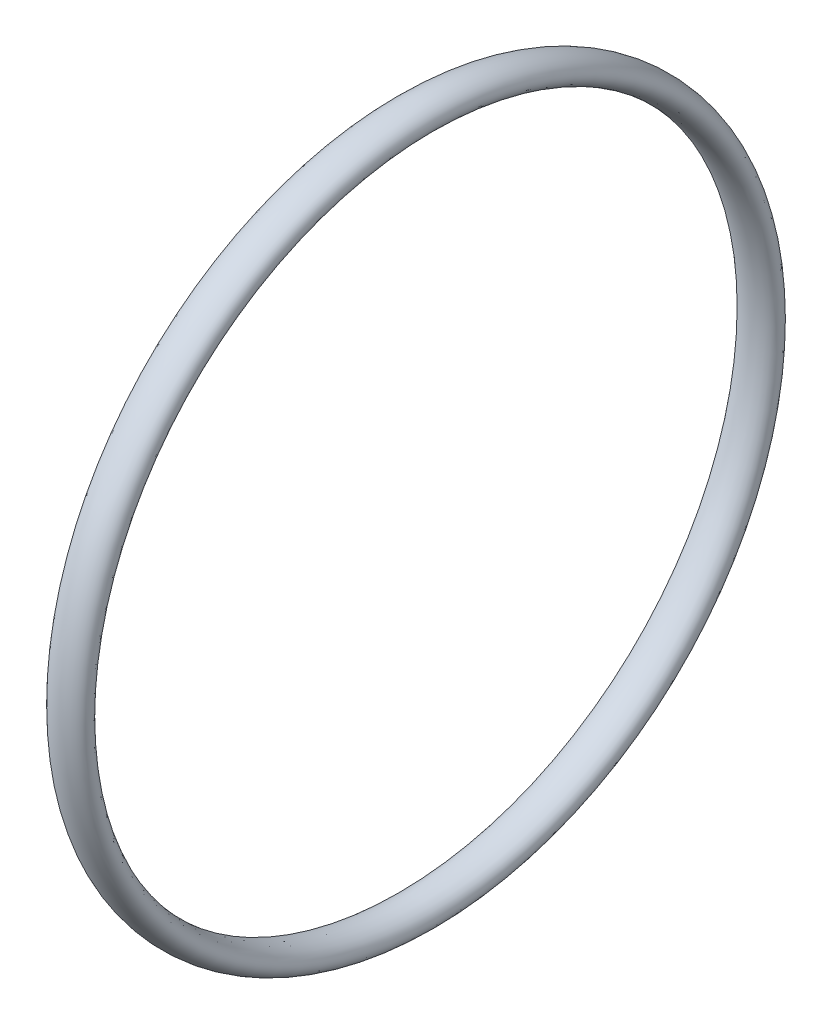
SolidWorks part; units mm, degrees
ref_plane "Front Plane" through (0, 0, 0) normal (0, 0, 1) x (1, 0, 0)
ref_plane "Top Plane" through (0, 0, 0) normal (0, 1, 0) x (1, 0, 0)
ref_plane "Right Plane" through (0, 0, 0) normal (1, 0, 0) x (0, 0, -1)
ref_axis "Axis1" through (-88.99, 0, 0) along (1, 0, 0)
sketch "Sketch1" plane through (0, 0, 0) normal (0, 1, 0) x (1, 0, 0)
  ellipse E0 centre (0, 33.75) end of major axis (-2, 33.75) minor radius 1.25
  point P1 (0, 0)
  dimension "D1" = 33.75
  dimension "D2" = 4
  dimension "D3" = 2.5
revolve "Revolve1" add sketch "Sketch1" angle 360 about axis through (-88.99, 0, 0) along (1, 0, 0)
